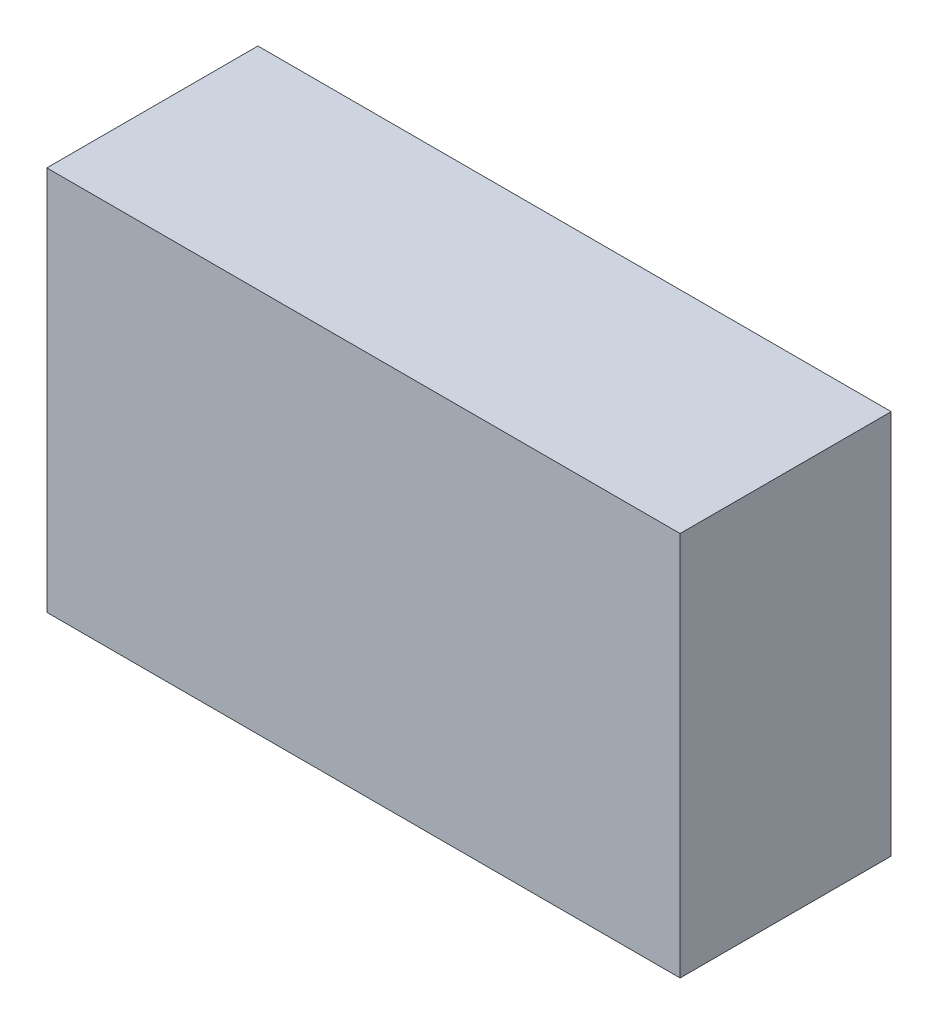
SolidWorks part; units mm, degrees
ref_plane "Front Plane" through (0, 0, 0) normal (0, 0, 1) x (1, 0, 0)
ref_plane "Top Plane" through (0, 0, 0) normal (0, 1, 0) x (1, 0, 0)
ref_plane "Right Plane" through (0, 0, 0) normal (1, 0, 0) x (0, 0, -1)
sketch "Sketch1" plane through (0, 0, 0) normal (0, 0, 1) x (1, 0, 0)
  line L1 (-25.5, -15.5) -> (25.5, -15.5)
  line L2 (-25.5, -15.5) -> (-25.5, 15.5)
  line L3 (-25.5, 15.5) -> (25.5, 15.5)
  line L4 (25.5, -15.5) -> (25.5, 15.5)
  line L5 (-25.5, -15.5) -> (25.5, 15.5) construction
  line L6 (-25.5, 15.5) -> (25.5, -15.5) construction
  point P0 (0, 0)
  dimension "D1" = 51
  dimension "D2" = 31
extrude "Boss-Extrude1" add sketch "Sketch1" along normal blind 17
